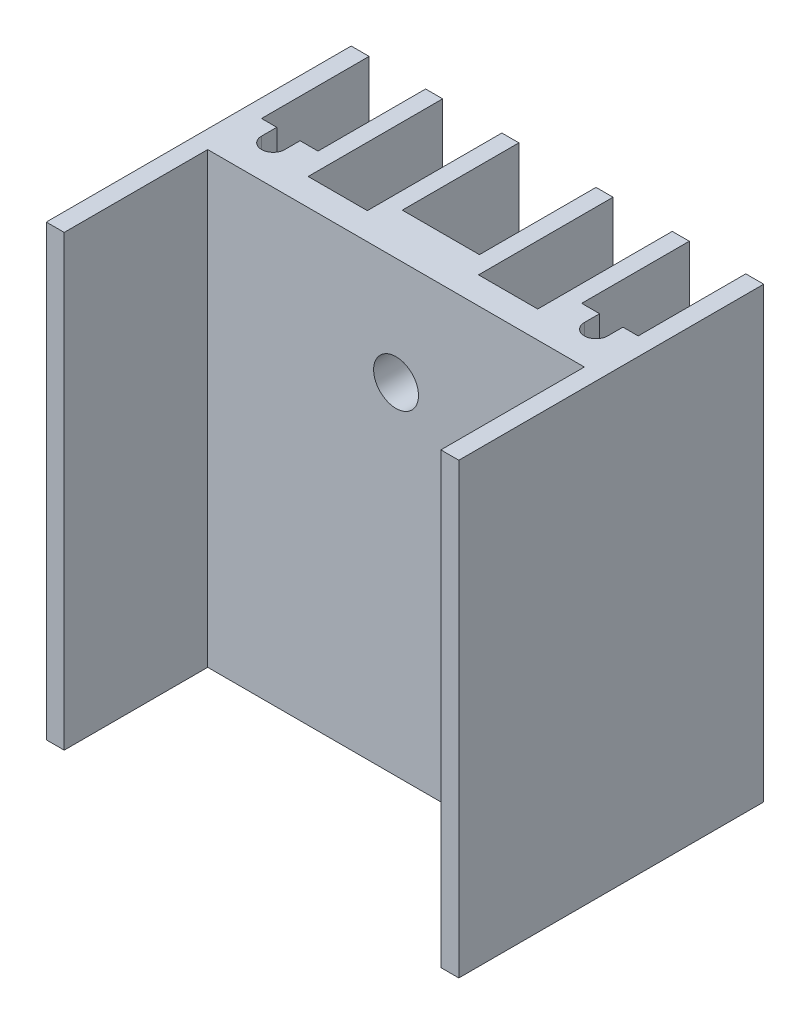
SolidWorks part; units mm, degrees
ref_plane "Front" through (0, 0, 0) normal (0, 0, 1) x (1, 0, 0)
ref_plane "Top" through (0, 0, 0) normal (0, 1, 0) x (1, 0, 0)
ref_plane "Right" through (0, 0, 0) normal (1, 0, 0) x (0, 0, -1)
sketch "Sketch1" plane through (0, 0, 0) normal (0, 1, 0) x (1, 0, 0)
  line L0 (0, 8.5) -> (0, 0) construction
  line L1 (-11.5, 8.5) -> (11.5, 8.5)
  line L2 (-11.5, 8.5) -> (-11.5, -8.5)
  line L3 (-11.5, -8.5) -> (11.5, -8.5)
  line L4 (11.5, 8.5) -> (11.5, -8.5)
  line L5 (0, 0) -> (11.5, 0) construction
  dimension "D1" = 23
  dimension "D2" = 17
extrude "Boss-Extrude1" add sketch "Sketch1" along normal blind 25
sketch "Sketch2" plane through (0, 25, 0) normal (0, 1, 0) x (1, 0, 0)
  line L0 (-11.5, -8.5) -> (11.5, -8.5) construction
  line L1 (-10.5, -8.5) -> (10.5, -8.5)
  line L2 (-10.5, -8.5) -> (-10.5, -0.5)
  line L3 (-10.5, -0.5) -> (10.5, -0.5)
  line L4 (10.5, -8.5) -> (10.5, -0.5)
  line L5 (11.5, 8.5) -> (-11.5, 8.5) construction
  line L6 (-10.5, 8.5) -> (-7.35, 8.5)
  line L7 (-10.5, 8.5) -> (-10.5, 2.5)
  line L8 (-10.5, 2.5) -> (-7.35, 2.5)
  line L9 (-7.35, 8.5) -> (-7.35, 2.5)
  line L10 (0, 0) -> (0, 11.5104) construction
  line L11 (-6.4, 8.5) -> (-3.1, 8.5)
  line L12 (-6.4, 8.5) -> (-6.4, 1)
  line L13 (-6.4, 1) -> (-3.1, 1)
  line L14 (-3.1, 8.5) -> (-3.1, 1)
  line L15 (-2.15, 8.5) -> (2.15, 8.5)
  line L16 (-2.15, 8.5) -> (-2.15, 2)
  line L17 (-2.15, 2) -> (2.15, 2)
  line L18 (2.15, 8.5) -> (2.15, 2)
  line L19 (-7.35, 2.5) -> (-6.4, 2.5) construction
  line L20 (-3.1, 2.5) -> (-2.15, 2.5) construction
  line L21 (3.1, 8.5) -> (3.1, 1)
  line L22 (6.4, 1) -> (3.1, 1)
  line L23 (6.4, 8.5) -> (6.4, 1)
  line L24 (6.4, 8.5) -> (3.1, 8.5)
  line L25 (7.35, 8.5) -> (7.35, 2.5)
  line L26 (10.5, 2.5) -> (7.35, 2.5)
  line L27 (10.5, 8.5) -> (10.5, 2.5)
  line L28 (10.5, 8.5) -> (7.35, 8.5)
  point P6 (0, -0.5)
  dimension "D1" = 21
  dimension "D2" = 8
  dimension "D3" = 6
  dimension "D4" = 7.5
  dimension "D5" = 6.5
  dimension "D6" = 3.15
  dimension "D7" = 3.3
  dimension "D8" = 4.3
extrude "Cut-Extrude1" cut sketch "Sketch2" against normal through all
sketch "Sketch3" plane through (0, 25, 0) normal (0, 1, 0) x (1, 0, 0)
  line L0 (0, 0) -> (0, 7.5042) construction
  line L1 (8.35, 2.5) -> (8.35, 1.65)
  line L2 (7.35, 2.5) -> (10.5, 2.5) construction
  line L3 (9.65, 1.65) -> (9.65, 2.5)
  line L4 (9.65, 2.5) -> (8.35, 2.5)
  line L5 (10.5, -0.5) -> (-10.5, -0.5) construction
  line L6 (-8.35, 2.5) -> (-8.35, 1.65)
  line L7 (-9.65, 2.5) -> (-8.35, 2.5)
  line L8 (-9.65, 1.65) -> (-9.65, 2.5)
  arc A0 (8.35, 1.65) -> (9.65, 1.65) centre (9, 1.65) ccw
  arc A1 (-8.35, 1.65) -> (-9.65, 1.65) centre (-9, 1.65) cw
  dimension "D1" = 18
  dimension "D2" = 1.5
  dimension "D3" = 1.3
extrude "Cut-Extrude2" cut sketch "Sketch3" against normal through all
sketch "Sketch4" plane through (0, 0, 0.5) normal (0, 0, 1) x (1, 0, 0)
  line L0 (0, 25) -> (0, 19) construction
  line L1 (10.5, 25) -> (-10.5, 25) construction
  circle A0 centre (0, 19) radius 1.25
  dimension "D1" = 2.5
  dimension "D2" = 6
extrude "Cut-Extrude3" cut sketch "Sketch4" against normal up to next
